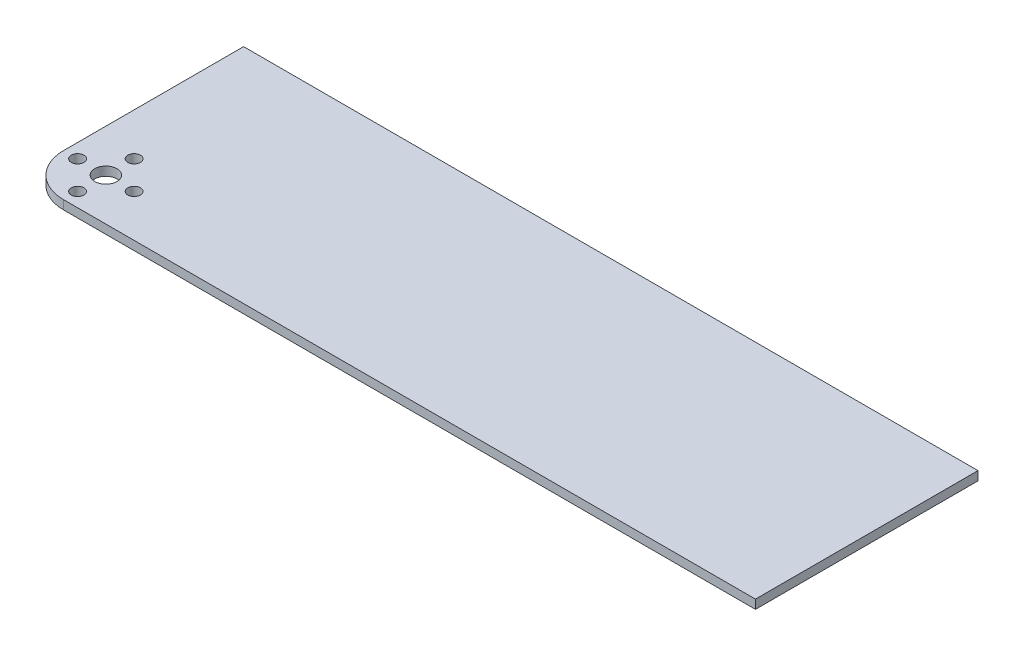
SolidWorks part; units mm, degrees
ref_plane "Front Plane" through (0, 0, 0) normal (0, 0, 1) x (1, 0, 0)
ref_plane "Top Plane" through (0, 0, 0) normal (0, 1, 0) x (1, 0, 0)
ref_plane "Right Plane" through (0, 0, 0) normal (1, 0, 0) x (0, 0, -1)
sketch "Sketch1" plane through (0, 0, 0) normal (0, 1, 0) x (1, 0, 0)
  line L1 (-82.5, -25) -> (82.5, -25)
  line L2 (-82.5, -25) -> (-82.5, 25)
  line L3 (-82.5, 25) -> (82.5, 25)
  line L4 (82.5, -25) -> (82.5, 25)
  line L5 (-82.5, -25) -> (82.5, 25) construction
  line L6 (-82.5, 25) -> (82.5, -25) construction
  circle A0 centre (-72.975, -15.475) radius 9.525
  point P0 (0, 0)
  point P8 (-70.8749, -13.5514)
  dimension "D3" = 19.05
  dimension "D1" = 165
  dimension "D2" = 50
  dimension "D4" = 9.525
  dimension "D5" = 9.525
extrude "Boss-Extrude1" add sketch "Sketch1" along normal blind 2 contours A0 L1 L4 L3 L2 | A0
sketch "Sketch2" plane through (0, 2, 0) normal (0, 1, 0) x (1, 0, 0)
  line L0 (-82.5, -15.475) -> (-82.5, 25) construction
  line L1 (-72.975, -25) -> (82.5, -25) construction
  line L2 (-106.7813, -15.475) -> (-39.2858, -15.475) construction
  circle A0 centre (-72.975, -15.475) radius 9.525
  circle A1 centre (-72.975, -9.125) radius 1.42
  circle A2 centre (-72.975, -15.475) radius 2.5
  circle A3 centre (-66.625, -15.475) radius 1.42
  circle A4 centre (-72.975, -21.825) radius 1.42
  circle A5 centre (-79.325, -15.475) radius 1.42
  point P20 (-72.975, -15.475)
  dimension "D1" = 19.05
  dimension "D4" = 2.84
  dimension "D5" = 5
  dimension "D2" = 9.525
  dimension "D3" = 9.525
  dimension "D6" = 6.35
  dimension "D7" = 9.525
  dimension "D8" = 4
extrude "Cut-Extrude2" cut sketch "Sketch2" against normal blind 6.35 contours L2 A3 | A3 L2 | A1 | L2 A5 | A5 L2 | A4 | L2 A2 | A2 L2
